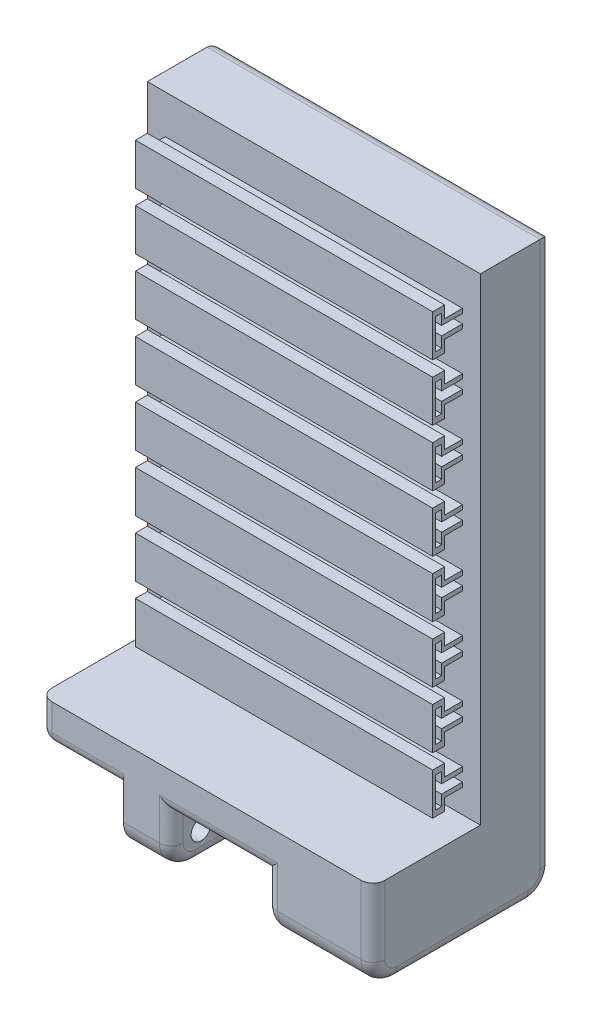
SolidWorks part; units mm, degrees
ref_plane "Front Plane" through (0, 0, 0) normal (0, 0, 1) x (1, 0, 0)
ref_plane "Top Plane" through (0, 0, 0) normal (0, 1, 0) x (1, 0, 0)
ref_plane "Right Plane" through (0, 0, 0) normal (1, 0, 0) x (0, 0, -1)
sketch "Sketch1" plane through (0, 0, 0) normal (0, 1, 0) x (1, 0, 0)
  line L1 (-27.9, 15) -> (27.9, 15)
  line L2 (-27.9, 15) -> (-27.9, -15)
  line L3 (-27.9, -15) -> (27.9, -15)
  line L4 (27.9, 15) -> (27.9, -15)
  line L5 (-27.9, 15) -> (27.9, -15) construction
  line L6 (-27.9, -15) -> (27.9, 15) construction
  point P0 (0, 0)
  dimension "D1" = 30
  dimension "D2" = 55.8
extrude "Boss-Extrude1" add sketch "Sketch1" along normal blind 6.5 contours L2 L3 L4 L1
sketch "Sketch2" plane through (0, 0, 0) normal (0, -1, 0) x (-1, 0, 0)
  line L0 (27.9, 15) -> (13.9, 15)
  line L1 (27.9, 15) -> (-27.9, 15) construction
  line L2 (13.9, 15) -> (13.9, -15)
  line L3 (27.9, -15) -> (-27.9, -15) construction
  line L4 (13.9, -15) -> (27.9, -15)
  line L5 (27.9, -15) -> (27.9, 15)
  line L6 (13.9, 15) -> (5.9, 15)
  line L7 (5.9, 15) -> (5.9, -15)
  line L8 (5.9, -15) -> (13.9, -15)
  line L9 (5.9, 15) -> (-9.9, 15)
  line L10 (-9.9, 15) -> (-9.9, -15)
  line L11 (-9.9, -15) -> (5.9, -15)
  line L12 (-9.9, 15) -> (-27.9, 15)
  line L13 (-27.9, 15) -> (-27.9, -15)
  line L14 (-27.9, -15) -> (-9.9, -15)
  line M8 (27.9, 15) -> (-27.9, 15)
  line M9 (-27.9, 15) -> (-27.9, -15)
  line M10 (-27.9, -15) -> (27.9, -15)
  dimension "D1" = 14
  dimension "D2" = 8
  dimension "D3" = 18
extrude "Boss-Extrude2" add sketch "Sketch2" along normal blind 9 contours L7 L2 M8 M10 | L10 M8 M9 M10
sketch "Sketch4" plane through (-13.9, 0, 0) normal (-1, 0, 0) x (0, 0, 1)
  line L0 (-15, -4.5) -> (-10, -4.5)
  line L1 (-15, -9) -> (-15, 0) construction
  line L2 (-10, -4.5) -> (0, -4.5)
  line L3 (0, -4.5) -> (10, -4.5)
  line L4 (10, -4.5) -> (15, -4.5)
  line L5 (15, -9) -> (15, 0) construction
  circle A0 centre (-10, -4.5) radius 1.675
  circle A1 centre (0, -4.5) radius 1.675
  circle A2 centre (10, -4.5) radius 1.675
  dimension "D4" = 3.35
  dimension "D5" = 3.35
  dimension "D6" = 3.35
  dimension "D1" = 5
  dimension "D2" = 10
  dimension "D3" = 10
extrude "Cut-Extrude1" cut sketch "Sketch4" against normal up to next contours L2 A0 L0 | L0 A0 L2 | L3 A1 L2 | L2 A1 L3 | L4 A2 L3 | L3 A2 L4
sketch "Sketch5" plane through (0, 6.5, 0) normal (0, 1, 0) x (1, 0, 0)
  line L5 (-27.9, 15) -> (27.9, 15)
  line L6 (27.9, 15) -> (27.9, 3)
  line L7 (27.9, 15) -> (27.9, -15) construction
  line L8 (27.9, 3) -> (-27.9, 3)
  line L9 (-27.9, 15) -> (-27.9, -15) construction
  line L10 (-27.9, 3) -> (-27.9, 15)
  dimension "D1" = 12
extrude "Boss-Extrude3" add sketch "Sketch5" along normal blind 80
sketch "Sketch6" plane through (-27.9, 0, 0) normal (-1, 0, 0) x (0, 0, 1)
  line L0 (15, 6.5) -> (-3, 10.5)
  line L1 (-3, 86.5) -> (-3, 6.5) construction
  line L2 (-3, 10.5) -> (-3, 6.5)
  line L3 (-3, 6.5) -> (15, 6.5)
  dimension "D1" = 4
extrude "Boss-Extrude4" [suppressed] add sketch "Sketch6" against normal through all
sketch "Sketch7" plane through (-27.9, 0, 0) normal (-1, 0, 0) x (0, 0, 1)
  line L0 (-3, 86.5) -> (-3, 80)
  line L1 (-3, 86.5) -> (-3, 6.5) construction
  line L2 (-3, 80) -> (-3, 77)
  line L3 (-3, 80) -> (0, 80)
  line L4 (0, 80) -> (0, 82)
  line L5 (0, 82) -> (2, 82)
  line L6 (2, 82) -> (2, 75)
  line L7 (2, 75) -> (0, 75)
  line L8 (0, 75) -> (0, 77)
  line L9 (0, 77) -> (-3, 77)
  line M7 (-3, 6.5) -> (-3, 86.5)
  dimension "D1" = 3
  dimension "D2" = 3
  dimension "D3" = 2
  dimension "D4" = 7
  dimension "D5" = 6.5
extrude "Boss-Extrude5" add sketch "Sketch7" against normal through all contours L9 L8 L7 L6 L5 L4 L3 M7
pattern_linear "LPattern1" count 8 spacing 9.5 along (0, -1, 0) of "Boss-Extrude5"
sketch "Sketch10" [suppressed] plane through (27.9, 0, 0) normal (1, 0, 0) x (0, 0, -1)
  line L0 (3, 86.5) -> (3, 10.5)
sketch "Sketch15" plane through (27.9, 0, 0) normal (1, 0, 0) x (0, 0, -1)
  line L0 (3, 80) -> (0, 80)
  line L1 (0, 80) -> (0, 82)
  line L2 (0, 82) -> (-2, 82)
  line L3 (-2, 82) -> (-2, 75)
  line L4 (-2, 75) -> (0, 75)
  line L5 (0, 75) -> (0, 77)
  line L6 (0, 77) -> (3, 77)
  line L7 (0, 77) -> (3, 77) construction
  line L8 (3, 77) -> (3, 80)
extrude "Cut-Extrude3" cut sketch "Sketch15" against normal blind 3
mirror "Mirror1" about plane through (0, 0, 0) normal (1, 0, 0) of "Cut-Extrude3"
pattern_linear "LPattern3" count 8 spacing 9.5 along (0, -1, 0) of "Mirror1", "Cut-Extrude3"
sketch "Sketch17" plane through (24.9, 0, 0) normal (1, 0, 0) x (0, 0, -1)
  line L0 (3, 78.5) -> (3, 77.75)
  line L1 (3, 77) -> (3, 80) construction
  line L2 (3, 86.5) -> (3, 6.5) construction
  line L3 (3, 78.5) -> (3, 79.25)
  line L4 (3, 77.75) -> (0, 77.75)
  line L5 (0, 77.75) -> (-0.5, 77.75)
  line L6 (-0.5, 77.75) -> (-0.5, 75.95)
  line L7 (-0.5, 75.95) -> (-1.5, 75.95)
  line L8 (-1.5, 75.95) -> (-1.5, 78.5)
  line L9 (-1.5, 78.5) -> (-1.5, 79.25)
  line L10 (-1.5, 79.25) -> (-1.5, 81.05)
  line L11 (-1.5, 81.05) -> (-0.5, 81.05)
  line L12 (-0.5, 81.05) -> (-0.5, 79.25)
  line L13 (-0.5, 79.25) -> (3, 79.25)
  dimension "D1" = 0.75
  dimension "D2" = 0.75
  dimension "D3" = 3
  dimension "D4" = 0.5
  dimension "D5" = 1.8
  dimension "D6" = 1
  dimension "D7" = 1.8
extrude "Cut-Extrude5" cut sketch "Sketch17" against normal up to next
pattern_linear "LPattern4" count 8 spacing 9.5 along (0, -1, 0) of "Cut-Extrude5"
fillet "Fillet1" radius 4 1 edges at (-9.9, -9, 15)
fillet "Fillet8" radius 4 3 edges at (18.9, -9, 15) (18.9, -9, -15) (-9.9, -9, -15)
fillet "Fillet9" radius 2 7 edges at (27.9, 0.75, 15) (27.9, -7.8284, 13.8284) (27.9, -9, 0) (27.9, -7.8284, -13.8284) (27.9, 40.75, -15) (-27.9, 43.25, -15) (0, 86.5, -15)
fillet "Fillet12" radius 2 4 edges at (-27.9, 0, 1) (-27.3142, 0, -14.4142) (-19.9, 0, -15) (2, 0, -15)
fillet "Fillet13" radius 2 4 edges at (-27.9, 4.25, 15) (-27.3142, 0.5858, 15) (-19.9, 0, 15) (2, 0, 15)
fillet "Fillet15" radius 2 5 edges at (-5.9, -1.5, -15) (-5.9, -7.8284, -13.8284) (-5.9, -1.5, 15) (-5.9, -7.8284, 13.8284) (-5.9, -9, 0)
fillet "Fillet16" radius 2 5 edges at (9.9, -1.5, -15) (9.9, -7.8284, -13.8284) (9.9, -1.5, 15) (9.9, -7.8284, 13.8284) (9.9, -9, 0)
